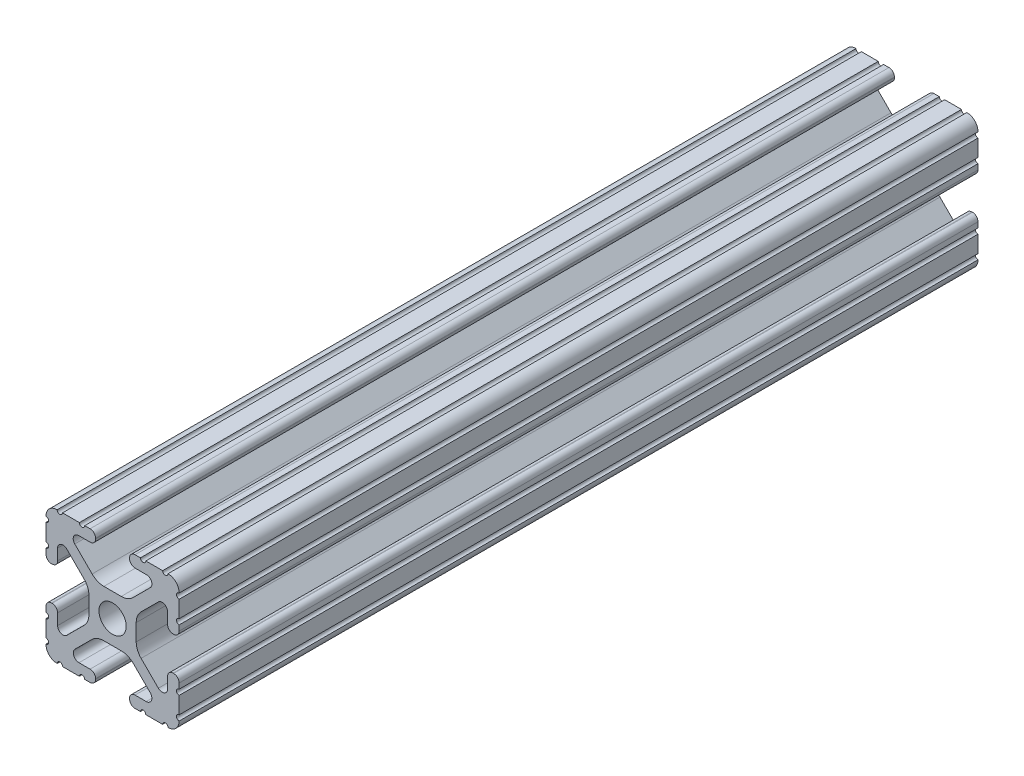
SolidWorks part; units mm, degrees
material "6061 Alloy"
ref_plane "Front Plane" through (0, 0, 0) normal (0, 0, 1) x (1, 0, 0)
ref_plane "Top Plane" through (0, 0, 0) normal (0, 1, 0) x (1, 0, 0)
ref_plane "Right Plane" through (0, 0, 0) normal (1, 0, 0) x (0, 0, -1)
sketch "Sketch1" plane through (0, 0, 0) normal (0, 0, 1) x (1, 0, 0)
  line L88 (-7.1797, -8.6452) -> (-3.9523, -5.4237)
  line L89 (-1.7093, -4.4958) -> (1.7093, -4.4958)
  line L90 (3.9523, -5.4237) -> (7.1797, -8.6452)
  line L91 (6.4164, -10.4902) -> (4.2875, -10.4902)
  line L92 (3.2385, -11.5392) -> (3.2385, -11.651)
  line L93 (4.2875, -12.7) -> (5.3171, -12.7)
  line L94 (6.3331, -12.7) -> (9.5504, -12.7)
  line L95 (12.7, -9.5504) -> (12.7, -6.3331)
  line L96 (12.7, -5.3171) -> (12.7, -4.2875)
  line L97 (11.651, -3.2385) -> (11.5392, -3.2385)
  line L98 (10.4902, -4.2875) -> (10.4902, -6.4021)
  line L99 (8.7371, -7.1294) -> (5.441, -3.8408)
  line L100 (4.5085, -1.5932) -> (4.5085, 1.5932)
  line L101 (5.441, 3.8408) -> (8.7371, 7.1294)
  line L102 (10.4902, 6.4021) -> (10.4902, 4.2875)
  line L103 (11.5392, 3.2385) -> (11.651, 3.2385)
  line L104 (12.7, 4.2875) -> (12.7, 5.3171)
  line L105 (12.7, 6.3331) -> (12.7, 9.5504)
  line L106 (9.5504, 12.7) -> (6.3331, 12.7)
  line L107 (5.3171, 12.7) -> (4.2875, 12.7)
  line L108 (3.2385, 11.651) -> (3.2385, 11.5392)
  line L109 (4.2875, 10.4902) -> (6.4768, 10.4902)
  line L110 (7.207, 8.7244) -> (3.8983, 5.4232)
  line L111 (1.6558, 4.4958) -> (-1.6558, 4.4958)
  line L112 (-3.8983, 5.4232) -> (-7.207, 8.7244)
  line L113 (-6.4768, 10.4902) -> (-4.2875, 10.4902)
  line L114 (-3.2385, 11.5392) -> (-3.2385, 11.651)
  line L115 (-4.2875, 12.7) -> (-5.3171, 12.7)
  line L116 (-6.3331, 12.7) -> (-9.5504, 12.7)
  line L117 (-12.7, 9.5504) -> (-12.7, 6.3331)
  line L118 (-12.7, 5.3171) -> (-12.7, 4.2875)
  line L119 (-11.651, 3.2385) -> (-11.5392, 3.2385)
  line L120 (-10.4902, 4.2875) -> (-10.4902, 6.4021)
  line L121 (-8.7371, 7.1294) -> (-5.441, 3.8408)
  line L122 (-4.5085, 1.5932) -> (-4.5085, -1.5932)
  line L123 (-5.441, -3.8408) -> (-8.7371, -7.1294)
  line L124 (-10.4902, -6.4021) -> (-10.4902, -4.2875)
  line L125 (-11.5392, -3.2385) -> (-11.651, -3.2385)
  line L126 (-12.7, -4.2875) -> (-12.7, -5.3171)
  line L127 (-12.7, -6.3331) -> (-12.7, -9.5504)
  line L128 (-9.5504, -12.7) -> (-6.3331, -12.7)
  line L129 (-5.3171, -12.7) -> (-4.2875, -12.7)
  line L130 (-3.2385, -11.651) -> (-3.2385, -11.5392)
  line L131 (-4.2875, -10.4902) -> (-6.4164, -10.4902)
  circle A1 centre (0, 0) radius 2.6035
  arc A104 (-7.1797, -8.6452) -> (-6.4164, -10.4902) centre (-6.4164, -9.4098) ccw
  arc A105 (-1.7093, -4.4958) -> (-3.9523, -5.4237) centre (-1.7093, -7.6708) ccw
  arc A106 (3.9523, -5.4237) -> (1.7093, -4.4958) centre (1.7093, -7.6708) ccw
  arc A107 (6.4164, -10.4902) -> (7.1797, -8.6452) centre (6.4164, -9.4098) ccw
  arc A108 (4.2875, -10.4902) -> (3.2385, -11.5392) centre (4.2875, -11.5392) ccw
  arc A109 (3.2385, -11.651) -> (4.2875, -12.7) centre (4.2875, -11.651) ccw
  arc A110 (6.3331, -12.7) -> (5.3171, -12.7) centre (5.8251, -12.7) ccw
  arc A111 (10.5664, -12.6998) -> (9.5504, -12.7) centre (10.0584, -12.7) ccw
  arc A112 (10.5664, -12.6998) -> (12.6998, -10.5664) centre (10.5918, -10.5918) ccw
  arc A113 (12.7, -9.5504) -> (12.6998, -10.5664) centre (12.7, -10.0584) ccw
  arc A114 (12.7, -5.3171) -> (12.7, -6.3331) centre (12.7, -5.8251) ccw
  arc A115 (12.7, -4.2875) -> (11.651, -3.2385) centre (11.651, -4.2875) ccw
  arc A116 (11.5392, -3.2385) -> (10.4902, -4.2875) centre (11.5392, -4.2875) ccw
  arc A117 (8.7371, -7.1294) -> (10.4902, -6.4021) centre (9.4628, -6.4021) ccw
  arc A118 (4.5085, -1.5932) -> (5.441, -3.8408) centre (7.6835, -1.5932) ccw
  arc A119 (5.441, 3.8408) -> (4.5085, 1.5932) centre (7.6835, 1.5932) ccw
  arc A120 (10.4902, 6.4021) -> (8.7371, 7.1294) centre (9.4628, 6.4021) ccw
  arc A121 (10.4902, 4.2875) -> (11.5392, 3.2385) centre (11.5392, 4.2875) ccw
  arc A122 (11.651, 3.2385) -> (12.7, 4.2875) centre (11.651, 4.2875) ccw
  arc A123 (12.7, 6.3331) -> (12.7, 5.3171) centre (12.7, 5.8251) ccw
  arc A124 (12.6998, 10.5664) -> (12.7, 9.5504) centre (12.7, 10.0584) ccw
  arc A125 (12.6998, 10.5664) -> (10.5664, 12.6998) centre (10.5918, 10.5918) ccw
  arc A126 (9.5504, 12.7) -> (10.5664, 12.6998) centre (10.0584, 12.7) ccw
  arc A127 (5.3171, 12.7) -> (6.3331, 12.7) centre (5.8251, 12.7) ccw
  arc A128 (4.2875, 12.7) -> (3.2385, 11.651) centre (4.2875, 11.651) ccw
  arc A129 (3.2385, 11.5392) -> (4.2875, 10.4902) centre (4.2875, 11.5392) ccw
  arc A130 (7.207, 8.7244) -> (6.4768, 10.4902) centre (6.4768, 9.4563) ccw
  arc A131 (1.6558, 4.4958) -> (3.8983, 5.4232) centre (1.6558, 7.6708) ccw
  arc A132 (-3.8983, 5.4232) -> (-1.6558, 4.4958) centre (-1.6558, 7.6708) ccw
  arc A133 (-6.4768, 10.4902) -> (-7.207, 8.7244) centre (-6.4768, 9.4563) ccw
  arc A134 (-4.2875, 10.4902) -> (-3.2385, 11.5392) centre (-4.2875, 11.5392) ccw
  arc A135 (-3.2385, 11.651) -> (-4.2875, 12.7) centre (-4.2875, 11.651) ccw
  arc A136 (-6.3331, 12.7) -> (-5.3171, 12.7) centre (-5.8251, 12.7) ccw
  arc A137 (-10.5664, 12.6998) -> (-9.5504, 12.7) centre (-10.0584, 12.7) ccw
  arc A138 (-10.5664, 12.6998) -> (-12.6998, 10.5664) centre (-10.5918, 10.5918) ccw
  arc A139 (-12.7, 9.5504) -> (-12.6998, 10.5664) centre (-12.7, 10.0584) ccw
  arc A140 (-12.7, 5.3171) -> (-12.7, 6.3331) centre (-12.7, 5.8251) ccw
  arc A141 (-12.7, 4.2875) -> (-11.651, 3.2385) centre (-11.651, 4.2875) ccw
  arc A142 (-11.5392, 3.2385) -> (-10.4902, 4.2875) centre (-11.5392, 4.2875) ccw
  arc A143 (-8.7371, 7.1294) -> (-10.4902, 6.4021) centre (-9.4628, 6.4021) ccw
  arc A144 (-4.5085, 1.5932) -> (-5.441, 3.8408) centre (-7.6835, 1.5932) ccw
  arc A145 (-5.441, -3.8408) -> (-4.5085, -1.5932) centre (-7.6835, -1.5932) ccw
  arc A146 (-10.4902, -6.4021) -> (-8.7371, -7.1294) centre (-9.4628, -6.4021) ccw
  arc A147 (-10.4902, -4.2875) -> (-11.5392, -3.2385) centre (-11.5392, -4.2875) ccw
  arc A148 (-11.651, -3.2385) -> (-12.7, -4.2875) centre (-11.651, -4.2875) ccw
  arc A149 (-12.7, -6.3331) -> (-12.7, -5.3171) centre (-12.7, -5.8251) ccw
  arc A150 (-12.6998, -10.5664) -> (-12.7, -9.5504) centre (-12.7, -10.0584) ccw
  arc A151 (-12.6998, -10.5664) -> (-10.5664, -12.6998) centre (-10.5918, -10.5918) ccw
  arc A152 (-9.5504, -12.7) -> (-10.5664, -12.6998) centre (-10.0584, -12.7) ccw
  arc A153 (-5.3171, -12.7) -> (-6.3331, -12.7) centre (-5.8251, -12.7) ccw
  arc A154 (-4.2875, -12.7) -> (-3.2385, -11.651) centre (-4.2875, -11.651) ccw
  arc A155 (-3.2385, -11.5392) -> (-4.2875, -10.4902) centre (-4.2875, -11.5392) ccw
extrude "Boss-Extrude1" add sketch "Sketch1" along normal mid plane 152.4
